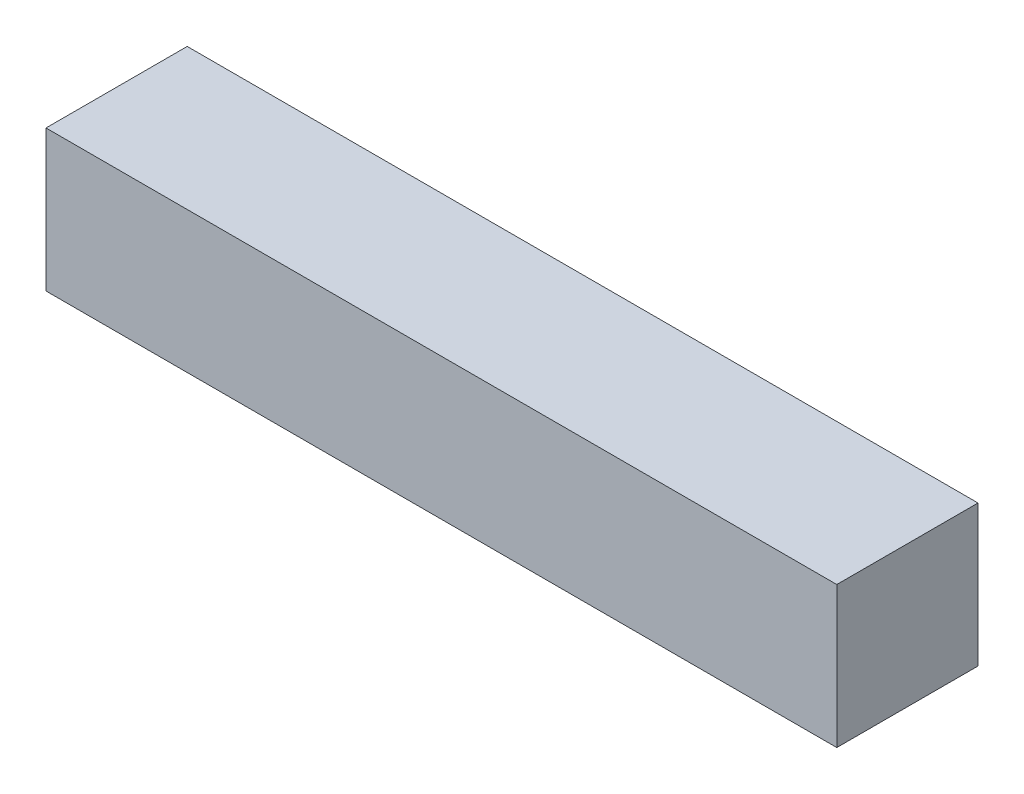
SolidWorks part; units mm, degrees
ref_plane "Front Plane" through (0, 0, 0) normal (0, 0, 1) x (1, 0, 0)
ref_plane "Top Plane" through (0, 0, 0) normal (0, 1, 0) x (1, 0, 0)
ref_plane "Right Plane" through (0, 0, 0) normal (1, 0, 0) x (0, 0, -1)
sketch "Sketch1" plane through (0, 0, 0) normal (0, 1, 0) x (1, 0, 0)
  line L2 (-11.2, -2) -> (11.2, -2)
  line L3 (-11.2, -2) -> (-11.2, 2)
  line L4 (-11.2, 2) -> (11.2, 2)
  line L5 (11.2, -2) -> (11.2, 2)
  line L6 (-11.2, -2) -> (11.2, 2) construction
  line L7 (-11.2, 2) -> (11.2, -2) construction
  point P1 (0, 0)
  dimension "D1" = 22.4
  dimension "D2" = 4
extrude "Boss-Extrude1" add sketch "Sketch1" along normal blind 4
